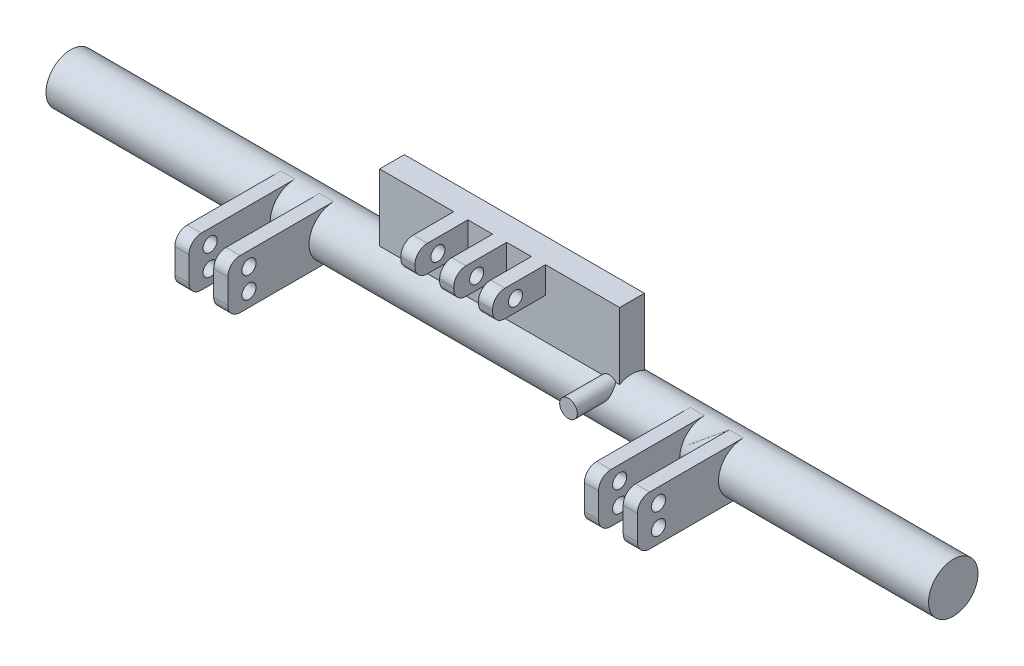
SolidWorks part; units mm, degrees
ref_plane "Front Plane" through (0, 0, 0) normal (0, 0, 1) x (1, 0, 0)
ref_plane "Top Plane" through (0, 0, 0) normal (0, 1, 0) x (1, 0, 0)
ref_plane "Right Plane" through (0, 0, 0) normal (1, 0, 0) x (0, 0, -1)
sketch "Sketch1" plane through (0, 0, 0) normal (0, 0, 1) x (1, 0, 0)
  line L0 (-125, 0) -> (125, 0)
  line L2 (-125, 7.5) -> (125, 7.5)
  line L3 (-125, 7.5) -> (-125, -7.5)
  line L4 (-125, -7.5) -> (125, -7.5)
  line L5 (125, 7.5) -> (125, -7.5)
  line L6 (-125, 7.5) -> (125, -7.5) construction
  line L7 (-125, -7.5) -> (125, 7.5) construction
  point P2 (0, 0)
  point P8 (0, 0)
  dimension "D1" = 250
  dimension "D2" = 15
revolve "Revolve-Thin1" add sketch "Sketch1" angle 360 about L0
sketch "Sketch2" plane through (0, 0, 0) normal (0, 1, 0) x (1, 0, 0)
  line L1 (-34, -3.5) -> (34, -3.5)
  line L2 (-34, -3.5) -> (-34, 3.5)
  line L3 (-34, 3.5) -> (34, 3.5)
  line L4 (34, -3.5) -> (34, 3.5)
  line L5 (-34, -3.5) -> (34, 3.5) construction
  line L6 (-34, 3.5) -> (34, -3.5) construction
  point P0 (0, 0)
extrude "Boss-Extrude1" add sketch "Sketch2" along normal blind 25
sketch "Sketch3" plane through (0, 0, 3.5) normal (0, 0, 1) x (1, 0, 0)
  line L1 (-13, 25) -> (-9, 25)
  line L2 (-13, 25) -> (-13, 17.5)
  line L3 (-13, 17.5) -> (-9, 17.5)
  line L4 (-9, 25) -> (-9, 17.5)
  line L5 (-2, 25) -> (2, 25)
  line L6 (-2, 25) -> (-2, 17.5)
  line L7 (-2, 17.5) -> (2, 17.5)
  line L8 (2, 25) -> (2, 17.5)
  line L13 (9, 25) -> (13, 25)
  line L14 (9, 25) -> (9, 17.5)
  line L15 (9, 17.5) -> (13, 17.5)
  line L16 (13, 25) -> (13, 17.5)
  point P3 (0, 17.5)
  dimension "D1" = 17.5
  dimension "D2" = 7.5
  dimension "D3" = 7
  dimension "D4" = 4
  dimension "D5" = 4
  dimension "D6" = 7
  dimension "D7" = 4
  dimension "D8" = 7.5
extrude "Boss-Extrude2" add sketch "Sketch3" along normal blind 15
sketch "Sketch4" plane through (-13, 0, 0) normal (-1, 0, 0) x (0, 0, 1)
  line L0 (3.5, 25) -> (3.5, 6.0622) construction
  line L1 (18.5, 17.5) -> (3.5, 17.5) construction
  circle A0 centre (12, 21) radius 2
  dimension "D1" = 8.5
  dimension "D2" = 3.5
fillet "Fillet1" radius 3.5 6 edges at (-11, 17.5, 18.5) (-11, 25, 18.5) (11, 17.5, 18.5) (11, 25, 18.5) (0, 17.5, 18.5) (0, 25, 18.5)
sketch "Sketch5" plane through (0, 0, 0) normal (0, 0, 1) x (1, 0, 0)
  line L0 (-34, 7) -> (-125, 7) construction
  line L1 (-54.5, 7) -> (-50.5, 7)
  line L2 (-54.5, 7) -> (-54.5, -7)
  line L3 (-54.5, -7) -> (-50.5, -7)
  line L4 (-50.5, 7) -> (-50.5, -7)
  line L5 (-61.5, 7) -> (-65.5, 7)
  line L6 (-61.5, 7) -> (-61.5, -7)
  line L7 (-61.5, -7) -> (-65.5, -7)
  line L8 (-65.5, 7) -> (-65.5, -7)
  line L9 (-125, -7) -> (125, -7) construction
  line L10 (0, -14.025) -> (0, 14.025) construction
  line L11 (65.5, 7) -> (65.5, -7)
  line L12 (61.5, -7) -> (65.5, -7)
  line L13 (61.5, 7) -> (61.5, -7)
  line L14 (61.5, 7) -> (65.5, 7)
  line L15 (50.5, 7) -> (50.5, -7)
  line L16 (54.5, -7) -> (50.5, -7)
  line L17 (54.5, 7) -> (54.5, -7)
  line L18 (54.5, 7) -> (50.5, 7)
  line L19 (125, 7) -> (34, 7) construction
  line L20 (13, 17.5) -> (13, 25) construction
  circle A0 centre (31, 4.5) radius 2.5
  point P4 (-50.5, 0)
  dimension "D6" = 2.5
  dimension "D1" = 14
  dimension "D2" = 4
  dimension "D3" = 54.5
  dimension "D4" = 4
  dimension "D5" = 7
  dimension "D7" = 18
extrude "Boss-Extrude3" add sketch "Sketch5" along normal blind 30
fillet "Fillet2" radius 3.5 8 edges at (63.5, -7, 30) (52.5, -7, 30) (52.5, 7, 30) (63.5, 7, 30) (-52.5, -7, 30) (-63.5, -7, 30) (-52.5, 7, 30) (-63.5, 7, 30)
sketch "Sketch6" plane through (-65.5, 0, 0) normal (-1, 0, 0) x (0, 0, 1)
  line L0 (26.5, 7) -> (0, 7) construction
  line L1 (30, 3.5) -> (30, -3.5) construction
  line L2 (26.5, -7) -> (0, -7) construction
  circle A0 centre (24, 3) radius 2
  circle A1 centre (24, -3) radius 2
  dimension "D1" = 4
  dimension "D3" = 4
  dimension "D2" = 6
  dimension "D4" = 6
extrude "Cut-Extrude1" cut sketch "Sketch6" along normal through all and the other way through all
extrude "Cut-Extrude2" cut sketch "Sketch4" against normal through all
sketch "Sketch7" plane through (0, 0, 30) normal (0, 0, 1) x (1, 0, 0)
  circle A0 centre (31, 4.5) radius 2.5
extrude "Cut-Extrude3" cut sketch "Sketch7" against normal blind 15
